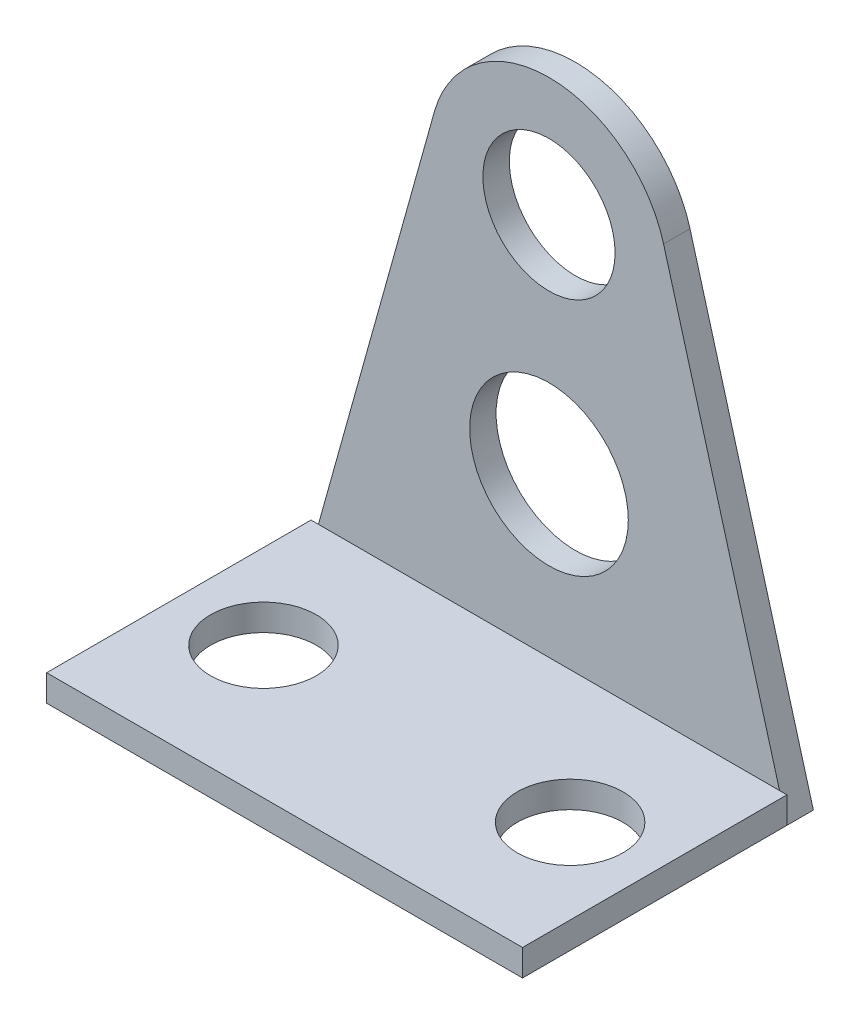
SolidWorks part; units mm, degrees
ref_plane "前视基准面" through (0, 0, 0) normal (0, 0, 1) x (1, 0, 0)
ref_plane "上视基准面" through (0, 0, 0) normal (0, 1, 0) x (1, 0, 0)
ref_plane "右视基准面" through (0, 0, 0) normal (1, 0, 0) x (0, 0, -1)
sketch "草图1" plane through (0, 0, 0) normal (0, 0, 1) x (1, 0, 0)
  line L0 (0, 0) -> (9, 0)
  line L1 (4.5, 0) -> (4.5, 3.5) construction
  line L2 (4.5, 3.5) -> (4.5, 7.75) construction
  line L3 (0, 0) -> (2.3329, 8.3551)
  line L4 (9, 0) -> (6.6671, 8.3551)
  circle A0 centre (4.5, 7.75) radius 1.25
  circle A1 centre (4.5, 3.5) radius 1.5
  arc A2 (6.6671, 8.3551) -> (2.3329, 8.3551) centre (4.5, 7.75) ccw
  dimension "D4" = 3
  dimension "D5" = 2.5
  dimension "D6" = 4.5
  dimension "D1" = 9
  dimension "D2" = 3.5
  dimension "D3" = 4.25
extrude "凸台-拉伸1" add sketch "草图1" along normal blind 0.5
sketch "草图2" plane through (0, 0, 0.5) normal (0, 0, 1) x (1, 0, 0)
  line L1 (0, 0) -> (9, 0)
  line L2 (0, 0) -> (0, 0.5)
  line L3 (0, 0.5) -> (9, 0.5)
  line L4 (9, 0) -> (9, 0.5)
  dimension "D1" = 0.5
extrude "凸台-拉伸2" add sketch "草图2" along normal blind 5
sketch "草图3" plane through (0, 0.5, 0) normal (0, 1, 0) x (1, 0, 0)
  line L0 (0, -3) -> (9, -3) construction
  line L1 (0, -5.5) -> (0, -0.5) construction
  line L2 (9, -5.5) -> (9, -0.5) construction
  circle A0 centre (1.6, -3) radius 1
  circle A1 centre (7.4, -3) radius 1
  dimension "D1" = 2
  dimension "D2" = 2
  dimension "D3" = 1.6
  dimension "D4" = 1.6
extrude "切除-拉伸1" cut sketch "草图3" against normal up to next
